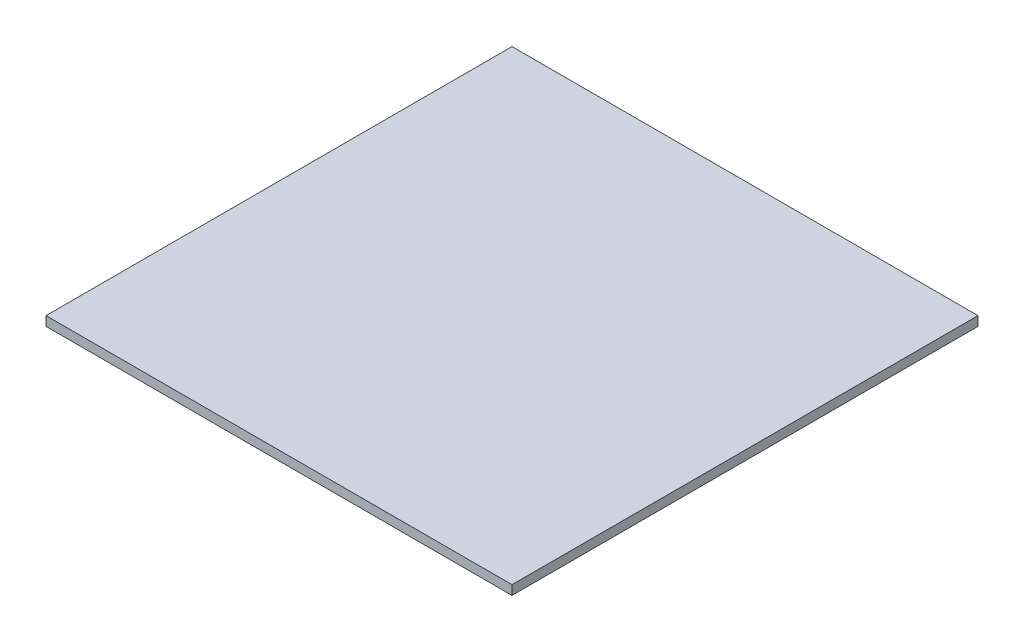
SolidWorks part; units mm, degrees
ref_plane "Plano frontal" through (0, 0, 0) normal (0, 0, 1) x (1, 0, 0)
ref_plane "Plano superior" through (0, 0, 0) normal (0, 1, 0) x (1, 0, 0)
ref_plane "Plano direito" through (0, 0, 0) normal (1, 0, 0) x (0, 0, -1)
sketch "Esboço1" plane through (0, 0, 0) normal (0, 1, 0) x (1, 0, 0)
  line L1 (-50, 50) -> (50, 50)
  line L2 (-50, 50) -> (-50, -50)
  line L3 (-50, -50) -> (50, -50)
  line L4 (50, 50) -> (50, -50)
  line L5 (-50, 50) -> (50, -50) construction
  line L6 (-50, -50) -> (50, 50) construction
  point P0 (0, 0)
  dimension "D1" = 100
  dimension "D2" = 100
extrude "Ressalto-extrusão1" add sketch "Esboço1" along normal blind 2
